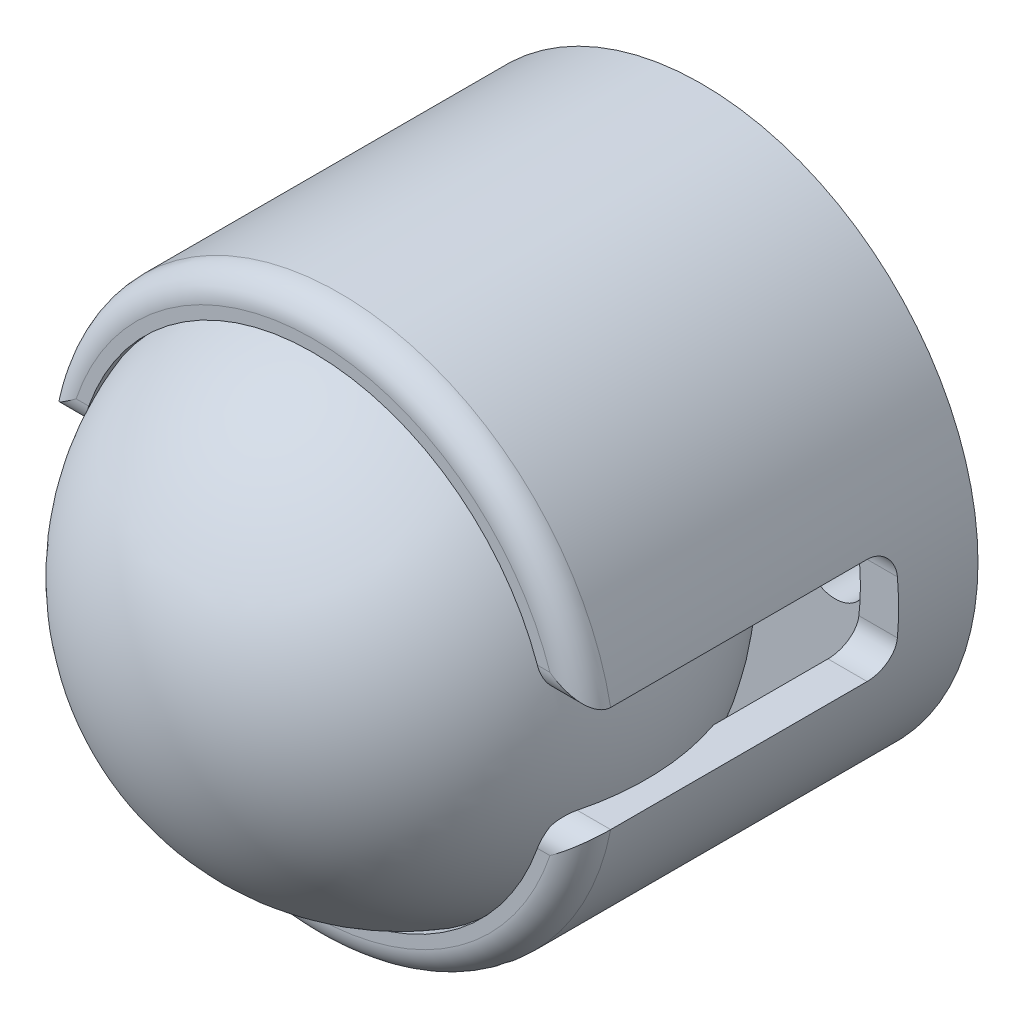
SolidWorks part; units mm, degrees
ref_plane "Front Plane" through (0, 0, 0) normal (0, 0, 1) x (1, 0, 0)
ref_plane "Top Plane" through (0, 0, 0) normal (0, 1, 0) x (1, 0, 0)
ref_plane "Right Plane" through (0, 0, 0) normal (1, 0, 0) x (0, 0, -1)
sketch "Sketch1" plane through (0, 0, 0) normal (0, 0, 1) x (1, 0, 0)
  line L0 (-7.75, 0) -> (7.75, 0) construction
  circle A0 centre (0, 0) radius 10.45
  circle A1 centre (-7.75, 0) radius 1.2
  circle A2 centre (7.75, 0) radius 1.2
  circle A3 centre (0, 0) radius 5.5
  dimension "D1" = 20.9
  dimension "D2" = 2.4
  dimension "D4" = 11
  dimension "D3" = 15.5
extrude "socket" add sketch "Sketch1" along normal blind 14.7
sketch "Sketch5" plane through (0, 0, 14.7) normal (0, 0, 1) x (1, 0, 0)
  circle A0 centre (0, 0) radius 9
  dimension "D1" = 18
extrude "counterbore" cut sketch "Sketch5" against normal blind 12
sketch "Sketch4" plane through (0, 0, 0) normal (1, 0, 0) x (0, 0, -1)
  line L0 (-14.7, 10.45) -> (-14.7, -10.45) construction
  line L1 (-3, -2) -> (-14.7, -2)
  line L2 (-3, -2) -> (-3, 2)
  line L3 (-3, 2) -> (-14.7, 2)
  line L4 (-14.7, -2) -> (-14.7, 2)
  line L5 (-3, -2) -> (-14.7, 2) construction
  line L6 (-3, 2) -> (-14.7, -2) construction
  point P0 (-8.85, 0)
  dimension "D1" = 4
  dimension "D2" = 3
extrude "side slot" cut sketch "Sketch4" against normal through all both and the other way through all
fillet "lip Fillet" radius 1 6 edges at (0, -10.45, 14.7) (0, 10.45, 14.7) (9.5159, 2, 14.7) (-9.5159, 2, 14.7) (-9.5159, -2, 14.7) (9.5159, -2, 14.7)
sketch "Sketch3" plane through (0, 0, 0) normal (1, 0, 0) x (0, 0, -1)
  line L1 (-20.875, 0) -> (-11.375, 0)
  line L3 (-11.375, 0) -> (-1.875, 0)
  arc A0 (-1.875, 0) -> (-20.875, 0) centre (-11.375, 0) ccw
  dimension "D1" = 9.5
  dimension "D2" = 11.375
revolve "rollerball" add sketch "Sketch3" angle 360 about L1
fillet "Fillet3" radius 1 4 edges at (9.5159, -2, 3) (-9.5159, -2, 3) (9.5159, 2, 3) (-9.5159, 2, 3)
ref_plane "caster ground contact" through (0, 0, 20.875) normal (0, 0, 1) x (1, 0, 0)
